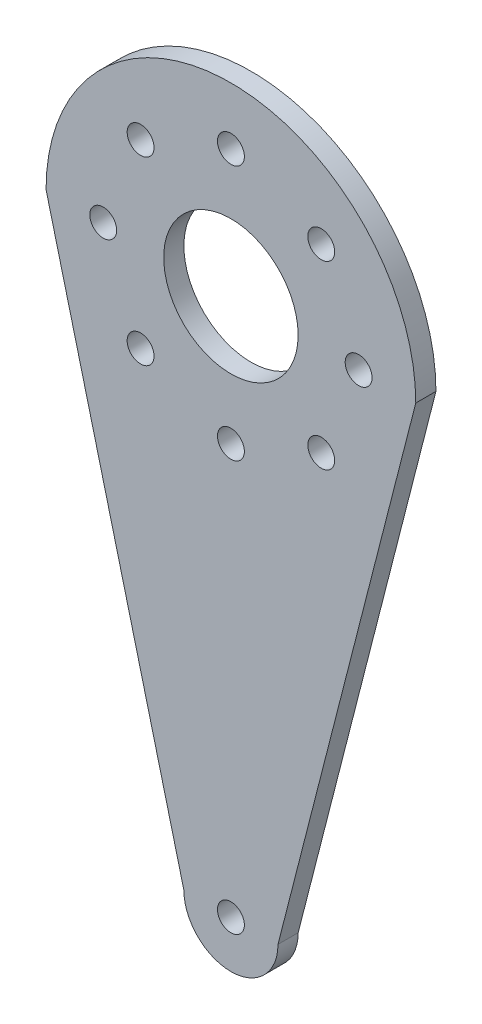
SolidWorks part; units mm, degrees
ref_plane "前视基准面" through (0, 0, 0) normal (0, 0, 1) x (1, 0, 0)
ref_plane "上视基准面" through (0, 0, 0) normal (0, 1, 0) x (1, 0, 0)
ref_plane "右视基准面" through (0, 0, 0) normal (1, 0, 0) x (0, 0, -1)
sketch "草图1" plane through (0, 0, 0) normal (0, 0, 1) x (1, 0, 0)
  line L50 (249.9534, 55.9629) -> (249.9534, 35.9629) construction
  line L71 (269.9534, 55.9629) -> (249.9534, 55.9629) construction
  line L261 (249.9534, 55.9629) -> (249.9534, -24.0371) construction
  line L266 (242.9534, -24.0371) -> (222.4534, 55.9629)
  line L267 (277.4534, 55.9629) -> (256.9534, -24.0371)
  circle A14 centre (249.9534, 55.9629) radius 10
  circle A15 centre (249.9534, 55.9629) radius 19 construction
  circle A24 centre (249.9534, 55.9629) radius 27.5 construction
  circle A28 centre (230.9534, 55.9629) radius 2
  circle A29 centre (236.5183, 69.398) radius 2
  circle A30 centre (249.9534, 74.9629) radius 2
  circle A31 centre (263.3884, 69.398) radius 2
  circle A32 centre (268.9534, 55.9629) radius 2
  circle A33 centre (263.3884, 42.5279) radius 2
  circle A34 centre (249.9534, 36.9629) radius 2
  circle A35 centre (236.5183, 42.5279) radius 2
  circle A36 centre (249.9534, -24.0371) radius 2
  circle A40 centre (249.9534, -24.0371) radius 7 construction
  arc A41 (222.4534, 55.9629) -> (277.4534, 55.9629) centre (249.9534, 55.9629) cw
  arc A42 (242.9534, -24.0371) -> (256.9534, -24.0371) centre (249.9534, -24.0371) ccw
  dimension "D1" = 8
  dimension "D2" = 20
extrude "凸台-拉伸1" add sketch "草图1" along normal blind 3
